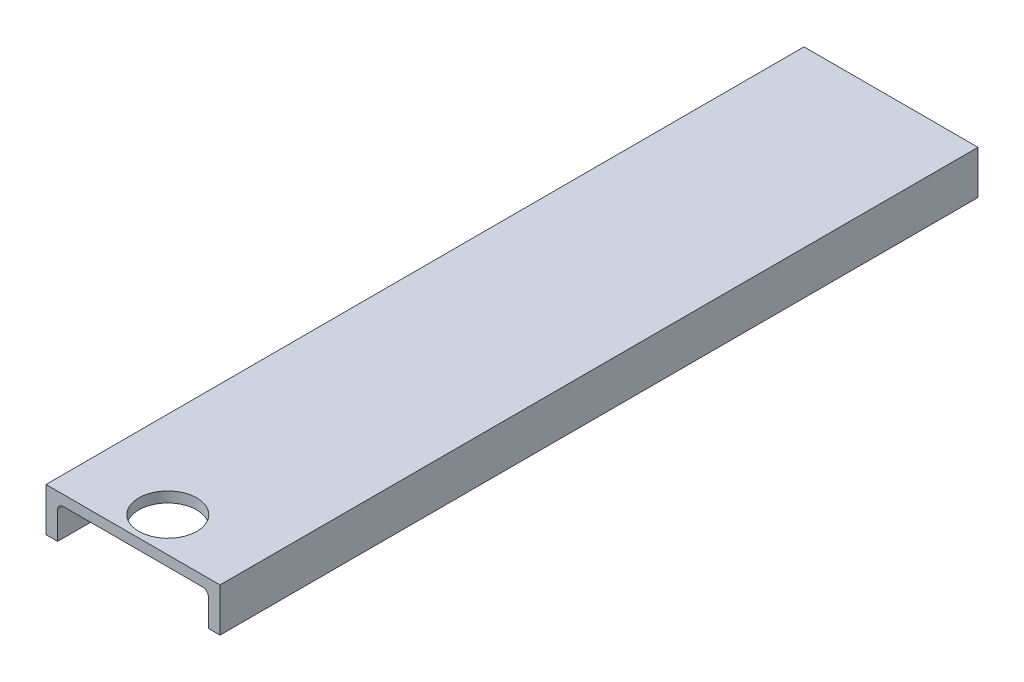
SolidWorks part; units mm, degrees
material "6061 Alloy"
ref_plane "Front Plane" through (0, 0, 0) normal (0, 0, 1) x (1, 0, 0)
ref_plane "Top Plane" through (0, 0, 0) normal (0, 1, 0) x (1, 0, 0)
ref_plane "Right Plane" through (0, 0, 0) normal (1, 0, 0) x (0, 0, -1)
sketch "Sketch1" plane through (0, 0, 0) normal (0, 0, 1) x (1, 0, 0)
  line L0 (0, 0) -> (38.1, 0)
  line L1 (38.1, 0) -> (38.1, -19.05)
  line L2 (38.1, -19.05) -> (33.02, -19.05)
  line L3 (33.02, -19.05) -> (33.02, -4.572)
  line L4 (33.02, -4.572) -> (-33.02, -4.572)
  line L5 (0, 0) -> (-38.1, 0)
  line L6 (-38.1, 0) -> (-38.1, -19.05)
  line L7 (-38.1, -19.05) -> (-33.02, -19.05)
  line L8 (-33.02, -19.05) -> (-33.02, -4.572)
extrude "Boss-Extrude1" add sketch "Sketch1" along normal blind 331.978
fillet "Fillet1" radius 2.54 1 edges at (-33.02, -4.572, 165.989)
fillet "Fillet2" radius 2.54 1 edges at (33.02, -4.572, 165.989)
sketch "Sketch2" plane through (0, 0, 0) normal (0, 1, 0) x (1, 0, 0)
  line L0 (38.1, -331.978) -> (-38.1, -331.978) construction
  circle A0 centre (0, -316.738) radius 12.7
  dimension "D1" = 15.24
  dimension "D2" = 25.4
extrude "Cut-Extrude1" cut sketch "Sketch2" against normal through all
